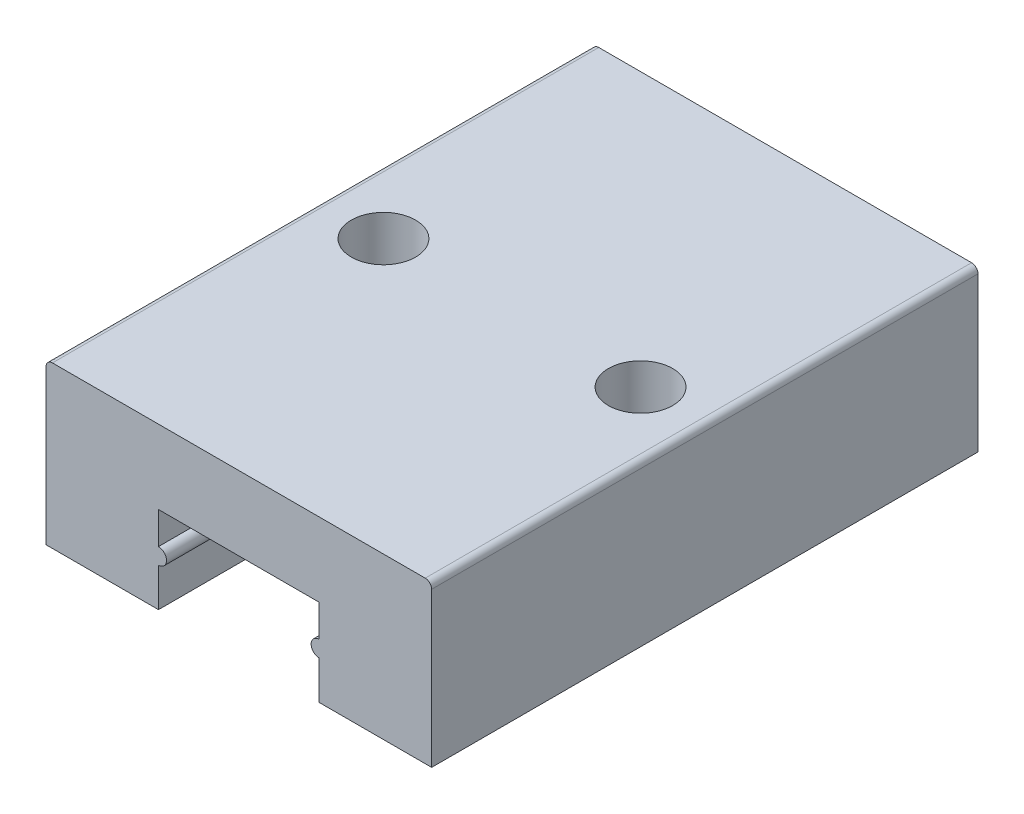
SolidWorks part; units mm, degrees
ref_plane "Front Plane" through (0, 0, 0) normal (0, 0, 1) x (1, 0, 0)
ref_plane "Top Plane" through (0, 0, 0) normal (0, 1, 0) x (1, 0, 0)
ref_plane "Right Plane" through (0, 0, 0) normal (1, 0, 0) x (0, 0, -1)
sketch "Sketch1" plane through (0, 0, 0) normal (0, 0, 1) x (1, 0, 0)
  line L0 (0, 0) -> (0, 4.9824) construction
  line L1 (2.5, 0) -> (6, 0)
  line L2 (2.5, 0) -> (2.5, 1.2)
  line L3 (2.5, 2.7) -> (-2.5, 2.7)
  line L4 (6, 0) -> (6, 5)
  line L5 (6, 5) -> (-6, 5)
  line L6 (2.5, 1.45) -> (0, 1.45) construction
  line L7 (2.5, 1.7) -> (2.5, 2.7)
  line L8 (-2.5, 1.7) -> (-2.5, 2.7)
  line L9 (-2.5, 0) -> (-2.5, 1.2)
  line L10 (-2.5, 0) -> (-6, 0)
  line L11 (-6, 0) -> (-6, 5)
  arc A0 (2.5, 1.7) -> (2.5, 1.2) centre (2.5, 1.45) ccw
  arc A1 (-2.5, 1.7) -> (-2.5, 1.2) centre (-2.5, 1.45) cw
  point P17 (0, 2.7)
  point P20 (0, 5)
  dimension "D5" = 1.25
  dimension "D6" = 0.5
  dimension "D1" = 6
  dimension "D2" = 5
  dimension "D3" = 2.3
  dimension "D4" = 2.5
extrude "Boss-Extrude1" add sketch "Sketch1" along normal mid plane 17
sketch "Sketch2" plane through (0, 5, 0) normal (0, 1, 0) x (1, 0, 0)
  line L0 (0, 8.5) -> (0, -8.5) construction
  line L1 (6, 8.5) -> (-6, 8.5) construction
  line L2 (6, -8.5) -> (-6, -8.5) construction
  line L3 (-6, 0) -> (6, 0) construction
  line L4 (-6, -8.5) -> (-6, 8.5) construction
  line L5 (6, -8.5) -> (6, 8.5) construction
  circle A0 centre (4, 0) radius 1
  circle A1 centre (-4, 0) radius 1
  dimension "D1" = 4
  dimension "D2" = 2
extrude "Cut-Extrude1" cut sketch "Sketch2" against normal blind 2
fillet "Fillet1" radius 0.2 2 edges at (6, 5, 0) (-6, 5, 0)
